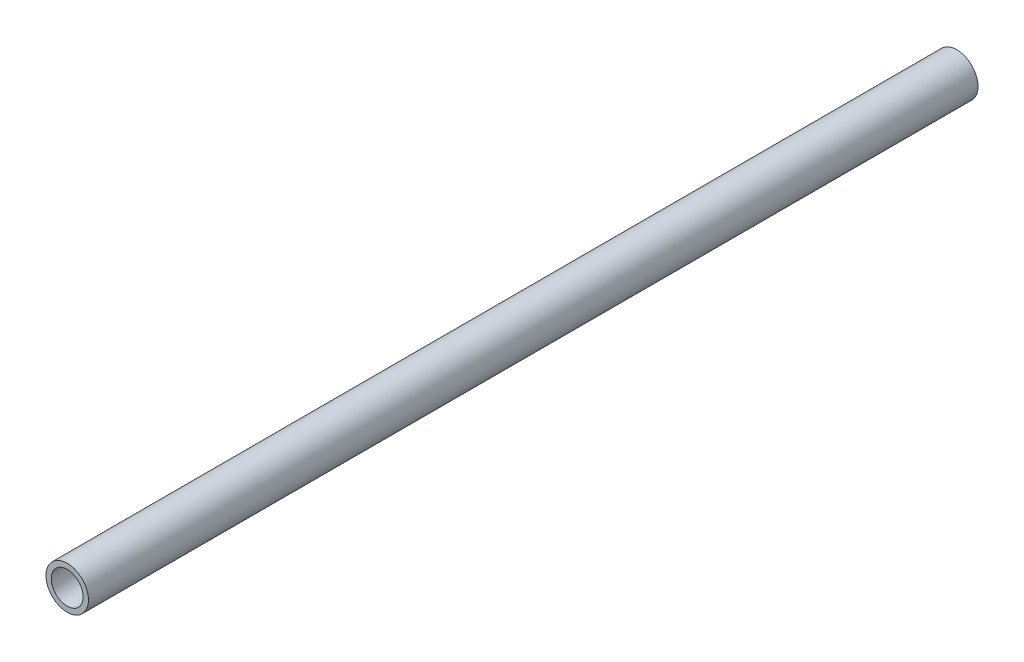
SolidWorks part; units mm, degrees
ref_plane "Front Plane" through (0, 0, 0) normal (0, 0, 1) x (1, 0, 0)
ref_plane "Top Plane" through (0, 0, 0) normal (0, 1, 0) x (1, 0, 0)
ref_plane "Right Plane" through (0, 0, 0) normal (1, 0, 0) x (0, 0, -1)
sketch "Sketch1" plane through (0, 0, 0) normal (0, 0, 1) x (1, 0, 0)
  circle A0 centre (0, 0) radius 8
  circle A1 centre (0, 0) radius 6
  dimension "D1" = 12
  dimension "D2" = 16
extrude "Boss-Extrude1" add sketch "Sketch1" along normal blind 335
